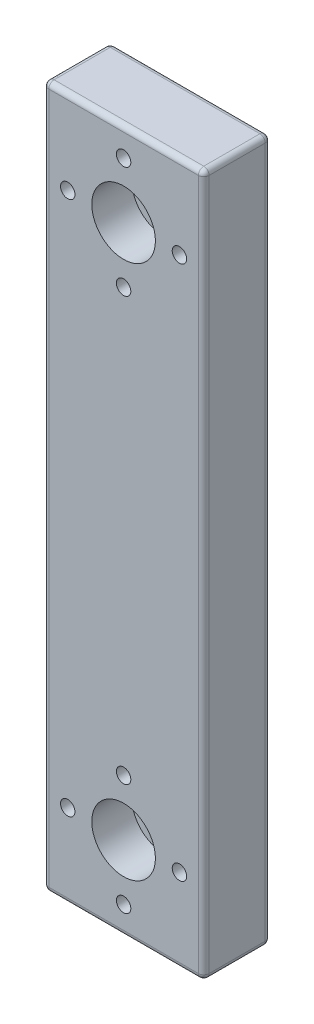
SolidWorks part; units mm, degrees
ref_plane "Front Plane" through (0, 0, 0) normal (1, 0, 0) x (0, 1, 0)
ref_plane "Top Plane" through (0, 0, 0) normal (0, 0, 1) x (0, 1, 0)
ref_plane "Right Plane" through (0, 0, 0) normal (0, 1, 0) x (-1, 0, 0)
sketch "Sketch1" plane through (0, 0, 0) normal (0, 0, 1) x (0, 1, 0)
  line L1 (166.751, -38.1) -> (-166.751, -38.1)
  line L2 (166.751, -38.1) -> (166.751, 38.1)
  line L3 (166.751, 38.1) -> (-166.751, 38.1)
  line L4 (-166.751, -38.1) -> (-166.751, 38.1)
  line L5 (166.751, -38.1) -> (-166.751, 38.1) construction
  line L6 (166.751, 38.1) -> (-166.751, -38.1) construction
  point P0 (0, 0)
  dimension "D1" = 76.2
  dimension "D2" = 333.502
extrude "Boss-Extrude1" add sketch "Sketch1" along normal blind 31.75 contours L3 L4 L1 L2
sketch "Sketch2" plane through (0, 0, 31.75) normal (0, 0, 1) x (1, 0, 0)
  circle A0 centre (0, 127) radius 15.113
  circle A1 centre (0, -127) radius 15.113
  dimension "D3" = 30.226
  dimension "D1" = 127
  dimension "D2" = 254
extrude "Cut-Extrude1" cut sketch "Sketch2" against normal blind 19.05
sketch "Sketch3" plane through (0, 0, 12.7) normal (0, 0, 1) x (1, 0, 0)
  circle A0 centre (0, -127) radius 10.287
  circle A1 centre (0, 127) radius 10.287
  dimension "D1" = 20.574
extrude "Cut-Extrude2" cut sketch "Sketch3" against normal through all
sketch "Sketch4" plane through (0, 0, 31.75) normal (0, 0, 1) x (1, 0, 0)
  circle A0 centre (0, 127) radius 26.543 construction
  circle A1 centre (0, -127) radius 26.543 construction
  circle A2 centre (-26.543, 127) radius 3.429
  circle A3 centre (0, 153.543) radius 3.429
  circle A4 centre (26.543, 127) radius 3.429
  circle A5 centre (0, 100.457) radius 3.429
  circle A6 centre (0, -100.457) radius 3.429
  circle A7 centre (26.543, -127) radius 3.429
  circle A8 centre (0, -153.543) radius 3.429
  circle A9 centre (-26.543, -127) radius 3.429
  dimension "D1" = 53.086
  dimension "D2" = 6.858
extrude "Cut-Extrude3" cut sketch "Sketch4" against normal through all
fillet "Fillet1" radius 2.54 12 edges at (0, -166.751, 31.75) (0, -166.751, 0) (-38.1, 0, 31.75) (-38.1, -166.751, 15.875) (-38.1, 0, 0) (0, 166.751, 31.75) (-38.1, 166.751, 15.875) (0, 166.751, 0) (38.1, -166.751, 15.875) (38.1, 0, 31.75) (38.1, 166.751, 15.875) (38.1, 0, 0)
equation "\"Span\"= 10in"
equation "\"Width\"= 3in"
equation "\"Thickness\"= 1.25in"
equation "\"EndMargin\"= 0.25in"
equation "\"FlangeDia\"= 2.625in"
equation "\"BoltCircle\"= 2.09375in"
equation "\"BoltHoleDia\"= 0.265625in"
equation "\"CboreDia\"= 1.1875in"
equation "\"CboreDepth\"= 0.75in"
equation "\"ThruDia\"= 0.8125in"
equation "\"Length\"= \"Span\" + \"FlangeDia\" + 2 * \"EndMargin\""
equation "\"EndDist\"= ( \"Length\" - \"Span\" ) / 2"
equation "\"EdgeDist\"= \"Width\" / 2 - \"BoltCircle\" / 2 - \"BoltHoleDia\" / 2"
equation "\"D1@Sketch1\"=\"Width\""
equation "\"D2@Sketch1\"=\"Length\""
equation "\"D1@Boss-Extrude1\"=\"Thickness\""
equation "\"D3@Sketch2\"=\"CboreDia\""
equation "\"D1@Cut-Extrude1\"=\"CboreDepth\""
equation "\"D1@Sketch3\"=\"ThruDia\""
equation "\"D1@Sketch4\"=\"BoltCircle\""
equation "\"D2@Sketch4\"=\"BoltHoleDia\""
